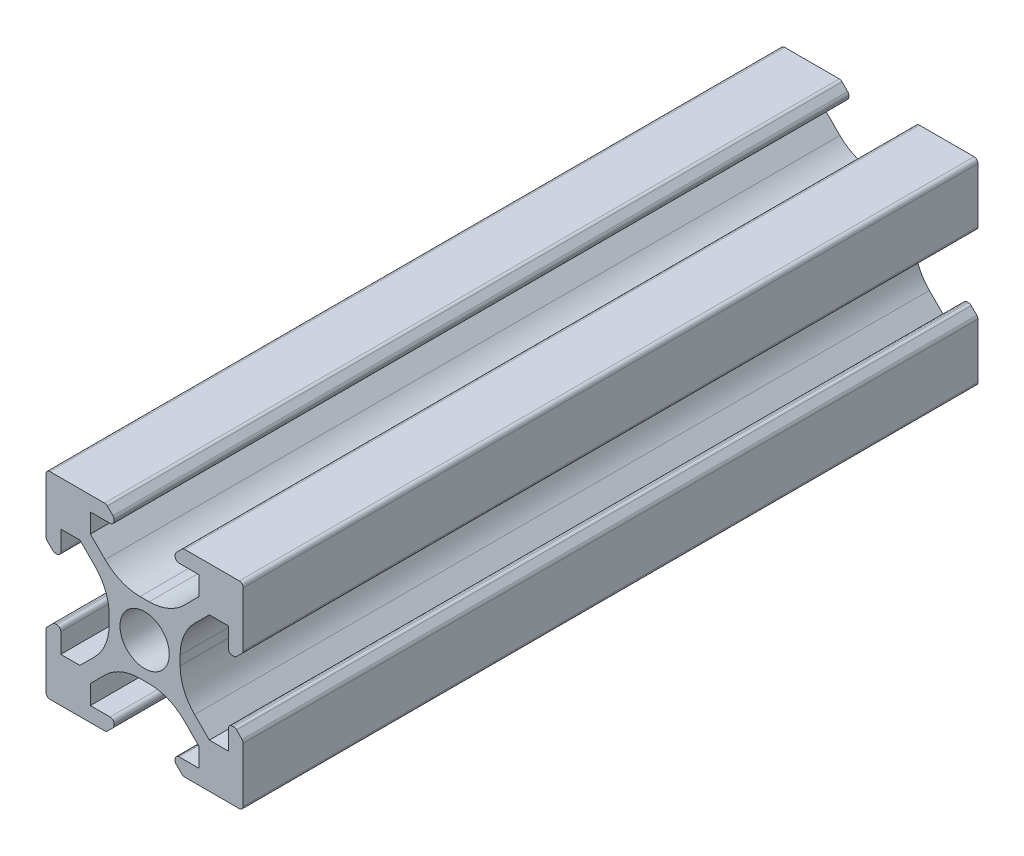
SolidWorks part; units mm, degrees
material "6063-T83"
ref_plane "Plano frontal" through (0, 0, 0) normal (0, 0, 1) x (1, 0, 0)
ref_plane "Plano superior" through (0, 0, 0) normal (0, 1, 0) x (1, 0, 0)
ref_plane "Plano direito" through (0, 0, 0) normal (1, 0, 0) x (0, 0, -1)
sketch "Esboço1" plane through (0, 0, 0) normal (0, 0, 1) x (1, 0, 0)
  line L0 (-9.0343, 3.1) -> (-8.9, 3.1)
  line L3 (-10, 10) -> (-4.0657, 10)
  line L5 (-10, -10) -> (10, 10) construction
  line L6 (-10, 10) -> (10, -10) construction
  line L7 (-8.5, 3.5) -> (-8.5, 5.5)
  line L8 (-10, 0) -> (10, 0) construction
  line L9 (0, 10) -> (0, -10) construction
  line L12 (-8.5, 5.5) -> (-6.5607, 5.5)
  line L15 (-6.5607, 5.5) -> (-5.0645, 4.0038)
  line L16 (-3.6, 0.4683) -> (-3.6, 0)
  line L17 (-0.4683, 3.6) -> (0, 3.6)
  line L18 (-5.5, 6.5607) -> (-4.0038, 5.0645)
  line L21 (-5.5, 8.5) -> (-5.5, 6.5607)
  line L24 (-3.5, 8.5) -> (-5.5, 8.5)
  line L25 (-3.1, 9.0343) -> (-3.1, 8.9)
  line L44 (-10, 4.0657) -> (-10, 10)
  line L45 (-9.8828, 3.7828) -> (-9.3172, 3.2172)
  line L46 (-3.7828, 9.8828) -> (-3.2172, 9.3172)
  line L47 (-3.6, 0) -> (-2.5, 0)
  line L48 (0, 3.6) -> (0, 2.5)
  arc A0 (-3.5, 8.5) -> (-3.1, 8.9) centre (-3.5, 8.9) ccw
  arc A1 (-3.7828, 9.8828) -> (-4.0657, 10) centre (-4.0657, 9.6) ccw
  arc A2 (-10, 4.0657) -> (-9.8828, 3.7828) centre (-9.6, 4.0657) ccw
  arc A3 (-8.5, 3.5) -> (-8.9, 3.1) centre (-8.9, 3.5) cw
  arc A4 (-3.2172, 9.3172) -> (-3.1, 9.0343) centre (-3.5, 9.0343) cw
  arc A5 (-9.3172, 3.2172) -> (-9.0343, 3.1) centre (-9.0343, 3.5) ccw
  arc A6 (-3.6, 0.4683) -> (-5.0645, 4.0038) centre (-8.6, 0.4683) ccw
  arc A7 (-4.0038, 5.0645) -> (-0.4683, 3.6) centre (-0.4683, 8.6) ccw
  circle A8 centre (0, 0) radius 2.5
  point P6 (-10, 3.1)
  point P28 (-3.1, 8.5)
  point P31 (-3.1, 10)
  point P33 (-3.9, 10)
  point P36 (-10, 3.9)
  point P39 (-8.5, 3.1)
  point P42 (-3.1, 9.2)
  point P45 (-9.2, 3.1)
  point P48 (-3.6, 2.5393)
  point P51 (-2.5393, 3.6)
  dimension "D5" = 10
  dimension "D9" = 0.4
  dimension "D10" = 0.4
  dimension "D11" = 5
  dimension "D12" = 5
  dimension "D13" = 5
  dimension "D1" = 6.9
  dimension "D2" = 1.5
  dimension "D3" = 3.6
  dimension "D4" = 1.5
  dimension "D6" = 2.4
  dimension "D7" = 3.6
  dimension "D8" = 45
extrude "Ressalto-extrusão1" add sketch "Esboço1" along normal blind 74.5
sketch "Esboço3" plane through (0, 0, 0) normal (1, 0, 0) x (0, 0, -1)
  line L0 (0, 0) -> (-74.5, 0) construction
  line L1 (-74.5, 2.5) -> (-74.5, 0) construction
pattern_circular "PadrãoCircular1" count 4 every 90 about axis through (0, 0, 0) along (0, 0, 1) of "Ressalto-extrusão1"
fillet "Filete1" radius 0.4 4 edges at (-10, -10, 37.25) (-10, 10, 37.25) (10, -10, 37.25) (10, 10, 37.25)
